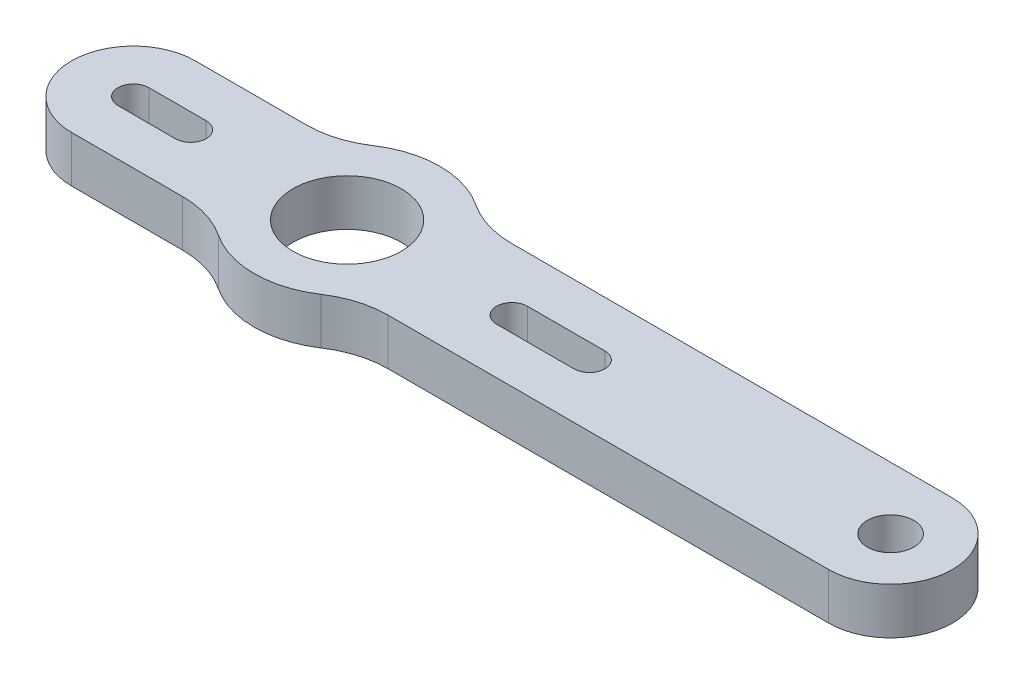
SolidWorks part; units mm, degrees
ref_plane "Plano frontal" through (0, 0, 0) normal (0, 0, 1) x (1, 0, 0)
ref_plane "Plano superior" through (0, 0, 0) normal (0, 1, 0) x (1, 0, 0)
ref_plane "Plano direito" through (0, 0, 0) normal (1, 0, 0) x (0, 0, -1)
sketch "Esboço1" plane through (0, 0, 0) normal (0, 1, 0) x (1, 0, 0)
  line L0 (0, 0) -> (48.9, 0) construction
  line L1 (0, 4) -> (48.9, 4)
  line L2 (0, -4) -> (48.9, -4)
  line L3 (0, 0) -> (3.7, 0) construction
  line L4 (0, 1) -> (3.7, 1)
  line L5 (0, -1) -> (3.7, -1)
  line L6 (24.45, 0) -> (29.45, 0) construction
  line L7 (24.45, 1) -> (29.45, 1)
  line L8 (24.45, -1) -> (29.45, -1)
  arc A0 (0, 4) -> (0, -4) centre (0, 0) ccw
  arc A1 (48.9, -4) -> (48.9, 4) centre (48.9, 0) ccw
  circle A2 centre (13.8, 0) radius 6
  arc A3 (0, 1) -> (0, -1) centre (0, 0) ccw
  arc A4 (3.7, -1) -> (3.7, 1) centre (3.7, 0) ccw
  arc A5 (24.45, 1) -> (24.45, -1) centre (24.45, 0) ccw
  arc A6 (29.45, -1) -> (29.45, 1) centre (29.45, 0) ccw
  point P3 (24.45, 0)
  point P13 (1.85, 0)
  point P20 (26.95, 0)
  dimension "D4" = 12
  dimension "D1" = 48.9
  dimension "D2" = 8
  dimension "D3" = 13.8
  dimension "D5" = 2
  dimension "D6" = 3.7
  dimension "D7" = 5
extrude "Ressalto-extrusão1" add sketch "Esboço1" along normal blind 3
hole_wizard "Furo de diâmetro Ø3.0 (3)1" positions "Esboço7" profile "Esboço8" hole size "Ø3.0" standard "ISO" end condition through all
sketch "Esboço7" plane through (0, 3, 0) normal (0, 1, 0) x (1, 0, 0)
  point P0 (48.9, 0)
sketch "Esboço8" plane through (48.9, 3, 0) normal (1, 0, 0) x (0, 0, 1)
  line L0 (0, 0) -> (0, 3)
  line L1 (0, 3) -> (1.5, 3)
  line L2 (1.5, 3) -> (1.5, 0)
  line L5 (1.5, 0) -> (0, 0)
  line L11 (0, -6.35) -> (0, 107.95) construction
  dimension "Thru Hole Dia." = 3
  dimension "Thru Hole Depth" = 3
hole_wizard "Furo de diâmetro Ø7.0 (7)1" positions "Esboço9" profile "Esboço10" hole size "Ø7.0" standard "ISO" end condition through all
sketch "Esboço9" plane through (0, 3, 0) normal (0, 1, 0) x (1, 0, 0)
  point P0 (13.8, 0)
sketch "Esboço10" plane through (13.8, 3, 0) normal (1, 0, 0) x (0, 0, 1)
  line L0 (0, 0) -> (0, 3)
  line L1 (0, 3) -> (3.5, 3)
  line L2 (3.5, 3) -> (3.5, 0)
  line L5 (3.5, 0) -> (0, 0)
  line L11 (0, -6.35) -> (0, 107.95) construction
  dimension "Thru Hole Dia." = 7
  dimension "Thru Hole Depth" = 3
fillet "Filete1" radius 6 4 edges at (9.3279, 1.5, -4) (18.2721, 1.5, -4) (18.2721, 1.5, 4) (9.3279, 1.5, 4)
